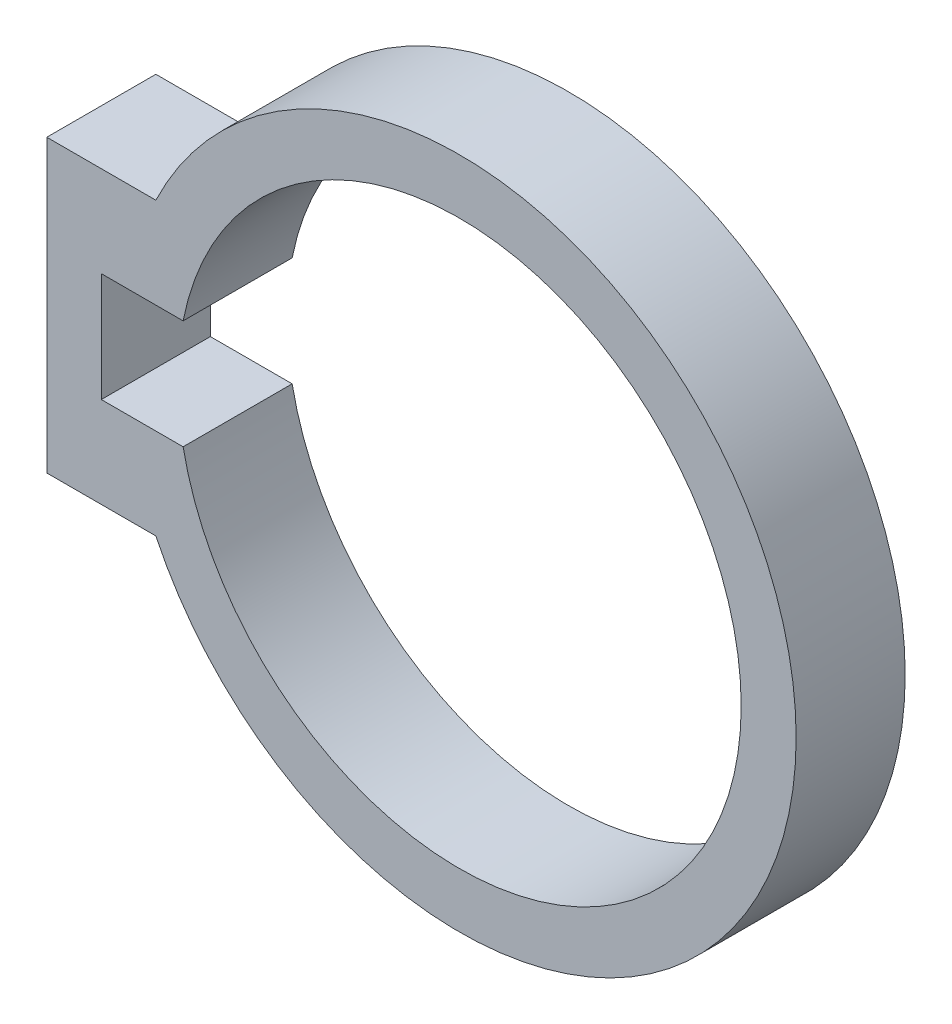
SolidWorks part; units mm, degrees
ref_plane "Plan de face" through (0, 0, 0) normal (0, 0, 1) x (1, 0, 0)
ref_plane "Plan de dessus" through (0, 0, 0) normal (0, 1, 0) x (1, 0, 0)
ref_plane "Plan de droite" through (0, 0, 0) normal (1, 0, 0) x (0, 0, -1)
sketch "Esquisse1" plane through (0, 0, 0) normal (0, 0, 1) x (1, 0, 0)
  line L1 (0, 0) -> (6, 0)
  line L3 (3, -5) -> (7.5, -5)
  line L6 (0, 0) -> (0, -16)
  line L8 (3, -5) -> (3, -11)
  line L9 (0, -16) -> (6, -16)
  line L11 (3, -11) -> (7.5, -11)
  arc A0 (6, 0) -> (6, -16) centre (22.7069, -8) cw
  arc A1 (7.5, -5) -> (7.5, -11) centre (22.7069, -8) cw
  dimension "D4" = 15.5
  dimension "D1" = 4.5
  dimension "D2" = 6
  dimension "D3" = 0
  dimension "D5" = 5
  dimension "D6" = 3
  dimension "D7" = 16
  dimension "D8" = 4.5
  dimension "D9" = 5
  dimension "D10" = 6
extrude "Boss.-Extru.1" add sketch "Esquisse1" along normal blind 6
equation "\"D2@Esquisse1\"=\"D1@Esquisse1\"+1.5"
equation "\"D10@Esquisse1\"=\"D1@Esquisse1\"+1.5"
